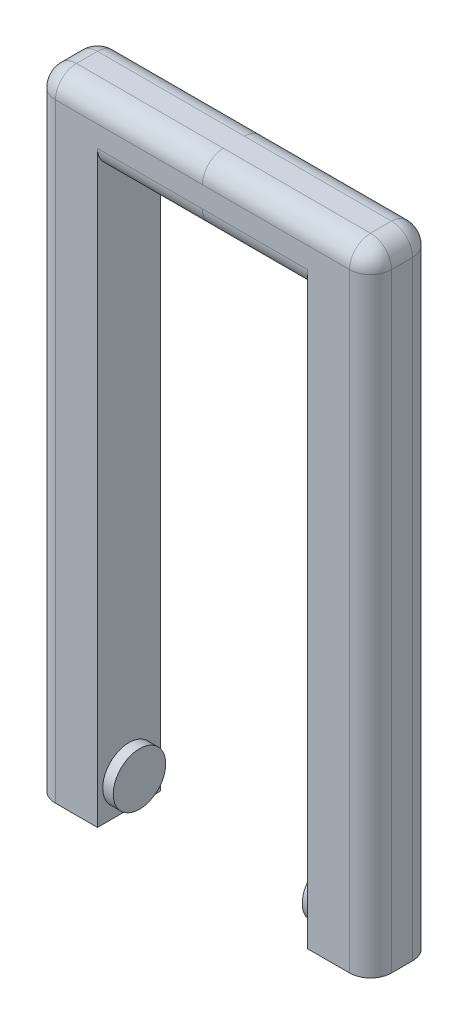
SolidWorks part; units mm, degrees
material "ABS"
ref_plane "Front Plane" through (0, 0, 0) normal (0, 0, 1) x (1, 0, 0)
ref_plane "Top Plane" through (0, 0, 0) normal (0, 1, 0) x (1, 0, 0)
ref_plane "Right Plane" through (0, 0, 0) normal (1, 0, 0) x (0, 0, -1)
sketch "Sketch3" plane through (0, 0, 0) normal (0, 0, 1) x (1, 0, 0)
  line L0 (-79.1698, 0) -> (99.171, 0) construction
  line L1 (0, 30) -> (-8, 30)
  line L2 (0, -55) -> (0, 55) construction
  line L3 (-8, 30) -> (-8, 18)
  line L4 (-8, 18) -> (-8, 0)
  line L5 (-8, 0) -> (-5, 0)
  line L6 (-5, 0) -> (-5, 27)
  line L7 (-5, 27) -> (0, 27)
  line L8 (0, 27) -> (0, 30)
  dimension "D1" = 30
  dimension "D2" = 5
  dimension "D3" = 3
  dimension "D4" = 3
  dimension "D5" = 18
extrude "Boss-Extrude1" add sketch "Sketch3" along normal blind 3
sketch "Sketch4" plane through (-5, 0, 0) normal (1, 0, 0) x (0, 0, -1)
  line L0 (-1.5, 0) -> (-1.5, 21.7071) construction
  line L1 (-3, 0) -> (0, 0) construction
  circle A0 centre (-1.5, 1.5) radius 1.25
  dimension "D1" = 2.5
  dimension "D2" = 1.5
extrude "Boss-Extrude2" add sketch "Sketch4" along normal blind 0.5
fillet "Fillet1" radius 1 2 edges at (-8, 15, 0) (-8, 15, 3)
fillet "Fillet2" radius 1 7 edges at (-7.7071, 30, 2.7071) (-8, 30, 1.5) (-7.7071, 30, 0.2929) (-2.5, 27, 0) (-2.5, 27, 3) (-3.5, 30, 3) (-3.5, 30, 0)
mirror "Mirror1" about plane through (0, 0, 0) normal (1, 0, 0) of "Fillet2", "Fillet1", "Boss-Extrude2", "Boss-Extrude1"
